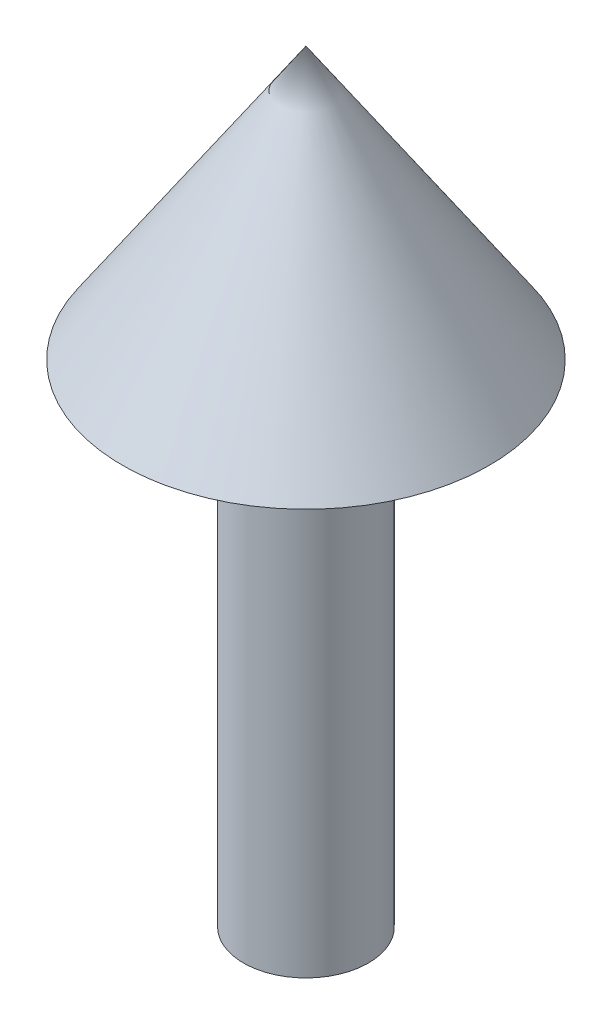
SolidWorks part; units mm, degrees
ref_plane "Front Plane" through (0, 0, 0) normal (0, 0, 1) x (1, 0, 0)
ref_plane "Top Plane" through (0, 0, 0) normal (0, 1, 0) x (1, 0, 0)
ref_plane "Right Plane" through (0, 0, 0) normal (1, 0, 0) x (0, 0, -1)
sketch "Sketch4" plane through (0, 0, 0) normal (0, 0, 1) x (1, 0, 0)
  line L0 (0, 31.4376) -> (0, 48.8128)
  line L1 (0, 48.8128) -> (11.731, 31.4376)
  line L2 (11.731, 31.4376) -> (0, 31.4376)
  line L4 (0, 31.4376) -> (4, 31.4376)
  line L5 (0, 31.4376) -> (0, 0)
  line L6 (0, 0) -> (4, 0)
  line L7 (4, 31.4376) -> (4, 0)
  dimension "D1" = 4
revolve "Revolve1" add sketch "Sketch4" angle 360 about L0
